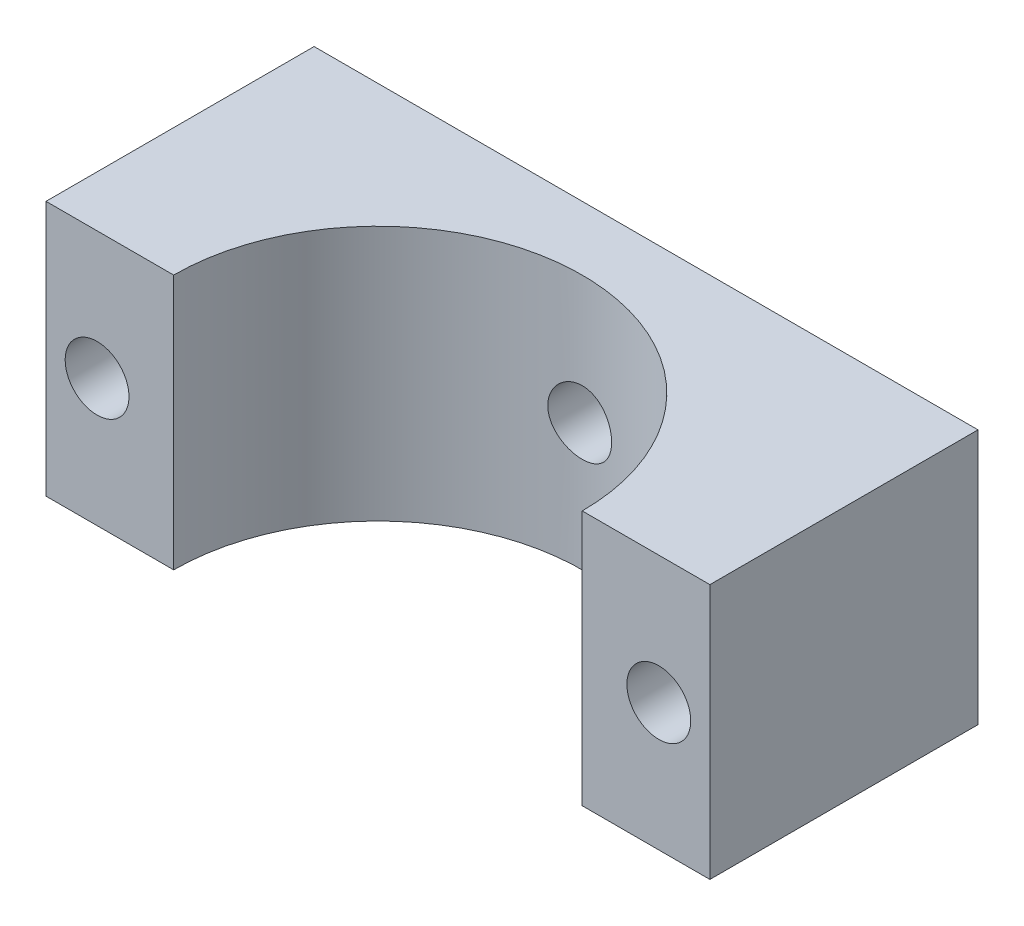
SolidWorks part; units mm, degrees
material "铬红铜，UNS C18200"
ref_plane "前视基准面" through (0, 0, 0) normal (0, 0, 1) x (1, 0, 0)
ref_plane "上视基准面" through (0, 0, 0) normal (0, 1, 0) x (1, 0, 0)
ref_plane "右视基准面" through (0, 0, 0) normal (1, 0, 0) x (0, 0, -1)
sketch "草图1" plane through (0, 0, 0) normal (0, 1, 0) x (1, 0, 0)
  line L0 (8, 0) -> (13, 0)
  line L1 (13, 0) -> (13, 10.5)
  line L2 (-8, 0) -> (-13, 0)
  line L3 (-13, 0) -> (-13, 10.5)
  line L4 (-13, 10.5) -> (13, 10.5)
  arc A0 (8, 0) -> (-8, 0) centre (0, 0) ccw
extrude "凸台-拉伸1" add sketch "草图1" along normal blind 10
sketch "草图2" plane through (0, 0, -10.5) normal (0, 0, -1) x (-1, 0, 0)
  circle A0 centre (-11, 5) radius 1.25
  circle A1 centre (0, 5) radius 1.25
  circle A2 centre (11, 5) radius 1.25
extrude "切除-拉伸2" cut sketch "草图2" against normal blind 13
